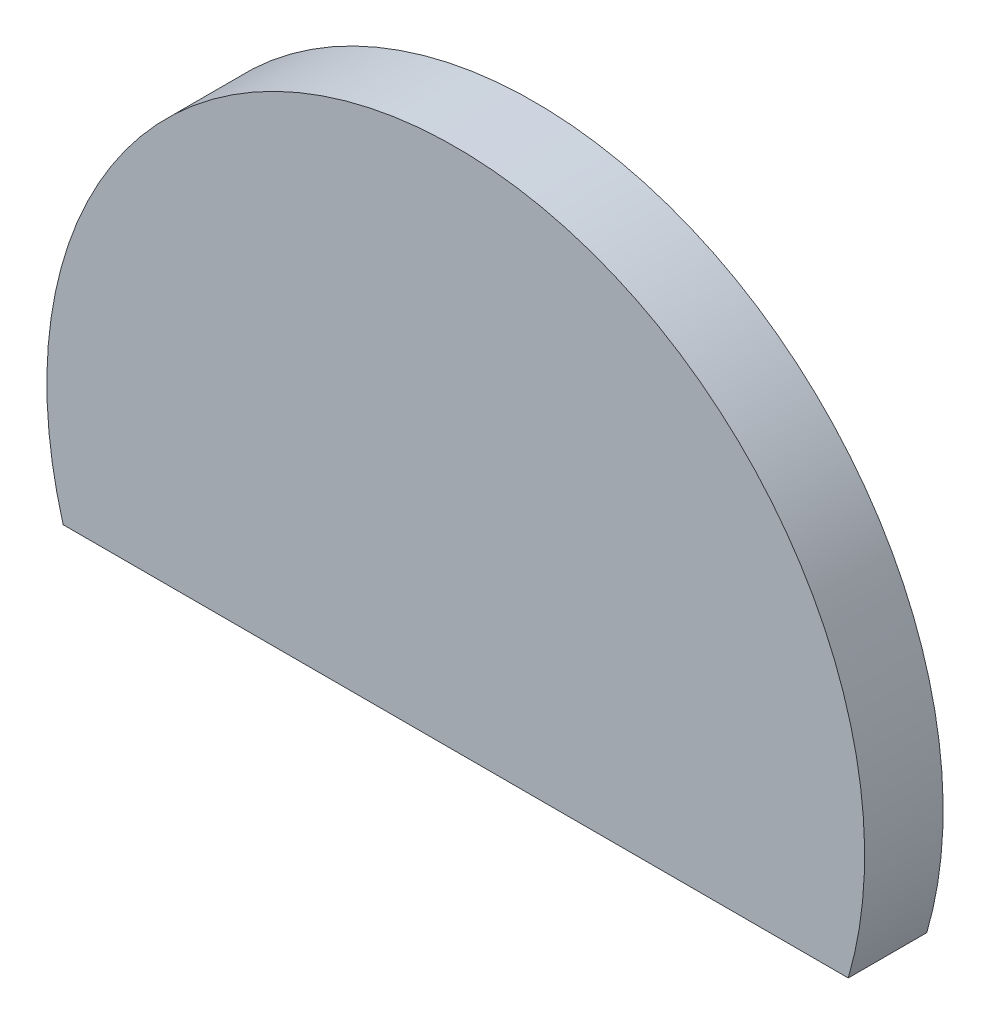
SolidWorks part; units mm, degrees
ref_plane "Front Plane" through (0, 0, 0) normal (0, 0, 1) x (1, 0, 0)
ref_plane "Top Plane" through (0, 0, 0) normal (0, 1, 0) x (1, 0, 0)
ref_plane "Right Plane" through (0, 0, 0) normal (1, 0, 0) x (0, 0, -1)
sketch "Sketch1" plane through (0, 0, 0) normal (0, 0, 1) x (1, 0, 0)
  line L4 (15, 180) -> (0, 180)
  line L9 (0, -11) -> (0, 11) construction
  line L10 (0, 180) -> (0, 200)
  arc A1 (0, 200) -> (15, 180) centre (0, 184.375) cw
  dimension "D1" = 15
  dimension "D5" = 20
extrude "Boss-Extrude1" add sketch "Sketch1" along normal blind 3
mirror "Mirror1" about plane through (0, 180, 3) normal (1, 0, 0) of "Boss-Extrude1"
